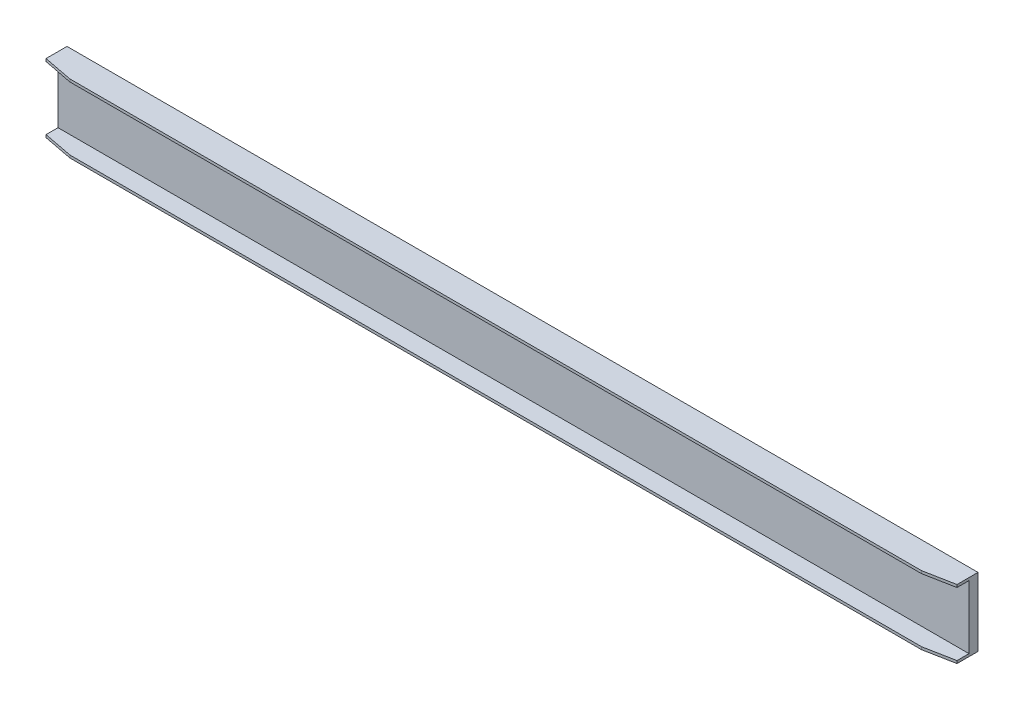
SolidWorks part; units mm, degrees
ref_plane "前视" through (0, 0, 0) normal (0, 0, 1) x (1, 0, 0)
ref_plane "上视" through (0, 0, 0) normal (0, 1, 0) x (1, 0, 0)
ref_plane "右视" through (0, 0, 0) normal (1, 0, 0) x (0, 0, -1)
sketch "草图1" plane through (0, 0, 0) normal (0, 0, 1) x (1, 0, 0)
  line L0 (0, 280.187) -> (0, -298.191) construction
  line L1 (-2057.2074, 0) -> (2116.7847, 0) construction
  line L2 (2116.7847, 80) -> (-2430.1435, 80) construction
  line L3 (-1995, 150) -> (1995, 150)
  line L5 (-1995, -150) -> (1995, -150)
  line L6 (1995, 150) -> (1995, -150)
  line L7 (-2430.1435, -80) -> (2116.7847, -80) construction
  line L8 (1940, 266.4652) -> (1940, -249.2739) construction
  line L9 (1860, -249.2739) -> (1860, 266.4652) construction
  line L10 (1060, 266.4652) -> (1060, -361.7988) construction
  line L11 (1780, 266.4652) -> (1780, -249.2739) construction
  line L12 (1780, -249.2739) -> (1700, -249.2739) construction
  line L13 (1700, -249.2739) -> (1700, 266.4652) construction
  line L14 (1540, 266.4652) -> (1540, -361.7988) construction
  line L15 (1380, 266.4652) -> (1380, -361.7988) construction
  line L16 (1220, -361.7988) -> (1220, 266.4652) construction
  line L17 (980, -361.7988) -> (980, 266.4652) construction
  line L18 (740, -361.7988) -> (740, 464.33) construction
  line L19 (820, 266.4652) -> (820, -361.7988) construction
  line L20 (580, -361.7988) -> (580, 266.4652) construction
  line L21 (420, -361.7988) -> (420, 266.4652) construction
  line L22 (300, -298.191) -> (300, 266.4652) construction
  line L23 (60, 280.187) -> (60, -298.191) construction
  line L24 (140, 280.187) -> (140, -298.191) construction
  line L25 (220, -298.191) -> (220, 280.187) construction
  line L26 (-1995, 150) -> (-1995, -150)
  circle A0 centre (1940, 80) radius 13
  circle A1 centre (1860, 80) radius 13
  circle A2 centre (1780, 80) radius 13
  circle A3 centre (1700, 80) radius 13
  circle A4 centre (1540, 80) radius 11.5
  circle A5 centre (1380, 80) radius 11.5
  circle A6 centre (1220, 80) radius 11.5
  circle A7 centre (1060, 80) radius 11.5
  circle A8 centre (980, 80) radius 11.5
  circle A9 centre (820, 80) radius 11.5
  circle A10 centre (740, 80) radius 11.5
  circle A11 centre (580, 80) radius 11.5
  circle A12 centre (980, 0) radius 11.5
  circle A13 centre (1060, 0) radius 11.5
  circle A14 centre (820, 0) radius 11.5
  circle A15 centre (740, 0) radius 11.5
  circle A16 centre (580, 0) radius 11.5
  circle A17 centre (1220, 0) radius 11.5
  circle A18 centre (1380, 0) radius 11.5
  circle A19 centre (1540, 0) radius 11.5
  circle A20 centre (1700, 0) radius 13
  circle A21 centre (1780, 0) radius 13
  circle A22 centre (1860, 0) radius 13
  circle A23 centre (1940, 0) radius 13
  circle A24 centre (420, 80) radius 11.5
  circle A25 centre (420, 0) radius 11.5
  circle A26 centre (300, 0) radius 11.5
  circle A27 centre (300, 80) radius 11.5
  circle A28 centre (220, 80) radius 11.5
  circle A29 centre (220, 0) radius 11.5
  circle A30 centre (140, 0) radius 13
  circle A31 centre (140, 80) radius 13
  circle A32 centre (60, 80) radius 13
  circle A33 centre (60, 0) radius 13
  circle A34 centre (1700, -80) radius 13
  circle A35 centre (1780, -80) radius 13
  circle A36 centre (1860, -80) radius 13
  circle A37 centre (1940, -80) radius 13
  circle A38 centre (580, -80) radius 11.5
  circle A39 centre (740, -80) radius 11.5
  circle A40 centre (820, -80) radius 11.5
  circle A41 centre (980, -80) radius 11.5
  circle A42 centre (1060, -80) radius 11.5
  circle A43 centre (1220, -80) radius 11.5
  circle A44 centre (1380, -80) radius 11.5
  circle A45 centre (1540, -80) radius 11.5
  circle A46 centre (220, -80) radius 11.5
  circle A47 centre (300, -80) radius 11.5
  circle A48 centre (420, -80) radius 11.5
  circle A49 centre (580, -80) radius 11.5
  circle A50 centre (60, -80) radius 13
  circle A51 centre (140, -80) radius 13
  circle A52 centre (-140, -80) radius 13
  circle A53 centre (-60, -80) radius 13
  circle A54 centre (-580, -80) radius 11.5
  circle A55 centre (-420, -80) radius 11.5
  circle A56 centre (-300, -80) radius 11.5
  circle A57 centre (-220, -80) radius 11.5
  circle A58 centre (-1540, -80) radius 11.5
  circle A59 centre (-1380, -80) radius 11.5
  circle A60 centre (-1220, -80) radius 11.5
  circle A61 centre (-1060, -80) radius 11.5
  circle A62 centre (-980, -80) radius 11.5
  circle A63 centre (-820, -80) radius 11.5
  circle A64 centre (-740, -80) radius 11.5
  circle A65 centre (-580, -80) radius 11.5
  circle A66 centre (-1940, -80) radius 13
  circle A67 centre (-1860, -80) radius 13
  circle A68 centre (-1780, -80) radius 13
  circle A69 centre (-1700, -80) radius 13
  circle A70 centre (-60, 0) radius 13
  circle A71 centre (-60, 80) radius 13
  circle A72 centre (-140, 80) radius 13
  circle A73 centre (-140, 0) radius 13
  circle A74 centre (-220, 0) radius 11.5
  circle A75 centre (-220, 80) radius 11.5
  circle A76 centre (-300, 80) radius 11.5
  circle A77 centre (-300, 0) radius 11.5
  circle A78 centre (-420, 0) radius 11.5
  circle A79 centre (-420, 80) radius 11.5
  circle A80 centre (-1940, 0) radius 13
  circle A81 centre (-1860, 0) radius 13
  circle A82 centre (-1780, 0) radius 13
  circle A83 centre (-1700, 0) radius 13
  circle A84 centre (-1540, 0) radius 11.5
  circle A85 centre (-1380, 0) radius 11.5
  circle A86 centre (-1220, 0) radius 11.5
  circle A87 centre (-580, 0) radius 11.5
  circle A88 centre (-740, 0) radius 11.5
  circle A89 centre (-820, 0) radius 11.5
  circle A90 centre (-1060, 0) radius 11.5
  circle A91 centre (-980, 0) radius 11.5
  circle A92 centre (-580, 80) radius 11.5
  circle A93 centre (-740, 80) radius 11.5
  circle A94 centre (-820, 80) radius 11.5
  circle A95 centre (-980, 80) radius 11.5
  circle A96 centre (-1060, 80) radius 11.5
  circle A97 centre (-1220, 80) radius 11.5
  circle A98 centre (-1380, 80) radius 11.5
  circle A99 centre (-1540, 80) radius 11.5
  circle A100 centre (-1700, 80) radius 13
  circle A101 centre (-1780, 80) radius 13
  circle A102 centre (-1860, 80) radius 13
  circle A103 centre (-1940, 80) radius 13
  dimension "D22" = 23
  dimension "D23" = 26
  dimension "D24" = 26
  dimension "D1" = 3990
  dimension "D2" = 300
  dimension "D3" = 70
  dimension "D4" = 80
  dimension "D5" = 55
  dimension "D6" = 80
  dimension "D7" = 80
  dimension "D8" = 80
  dimension "D9" = 455
  dimension "D10" = 160
  dimension "D11" = 160
  dimension "D12" = 160
  dimension "D13" = 80
  dimension "D14" = 160
  dimension "D15" = 80
  dimension "D16" = 160
  dimension "D17" = 160
  dimension "D18" = 120
  dimension "D19" = 60
  dimension "D20" = 80
  dimension "D21" = 80
extrude "基体-拉伸" add sketch "草图1" along normal blind 39.5
sketch "草图2" plane through (0, 0, 39.5) normal (0, 0, 1) x (1, 0, 0)
  line L0 (1995, -150) -> (1995, 150) construction
  line L1 (-1995, 150) -> (1995, 150)
  line L2 (-1995, 150) -> (-1995, 138.5)
  line L3 (-1995, 138.5) -> (1995, 138.5)
  line L4 (1995, 150) -> (1995, 138.5)
  line L5 (0, 0) -> (2507.3409, 0) construction
  line L6 (1995, -150) -> (1995, -138.5)
  line L7 (-1995, -138.5) -> (1995, -138.5)
  line L8 (-1995, -150) -> (-1995, -138.5)
  line L9 (-1995, -150) -> (1995, -150)
  dimension "D1" = 11.5
extrude "凸台-拉伸1" add sketch "草图2" along normal blind 77.5
sketch "草图3" plane through (0, 0, 0) normal (0, 0, -1) x (-1, 0, 0)
  line L0 (0, 0) -> (2381.8358, 0) construction
  line L1 (0, 348.8193) -> (0, -302.4645) construction
  line L2 (1300, 348.8193) -> (1300, -385.903) construction
  line L3 (1995, 150) -> (1995, -150) construction
  line L4 (900, 237.7997) -> (900, -385.903) construction
  line L5 (1265, 115) -> (1335, 115)
  line L6 (1265, 115) -> (1265, -115)
  line L7 (1265, -115) -> (1335, -115)
  line L8 (1335, 115) -> (1335, -115)
  line L9 (865, 115) -> (935, 115)
  line L10 (865, 115) -> (865, -115)
  line L11 (865, -115) -> (935, -115)
  line L12 (935, 115) -> (935, -115)
  line L13 (500, -385.903) -> (500, 237.7997) construction
  line L14 (-1265, 115) -> (-1335, 115)
  line L15 (535, -115) -> (465, -115)
  line L16 (535, -115) -> (535, 115)
  line L17 (535, 115) -> (465, 115)
  line L18 (465, -115) -> (465, 115)
  line L19 (-1335, 115) -> (-1335, -115)
  line L20 (-1265, 115) -> (-1265, -115)
  line L21 (-1265, -115) -> (-1335, -115)
  line L22 (-865, -115) -> (-935, -115)
  line L23 (-935, 115) -> (-935, -115)
  line L24 (-865, 115) -> (-935, 115)
  line L25 (-865, 115) -> (-865, -115)
  line L26 (-535, -115) -> (-535, 115)
  line L27 (-535, -115) -> (-465, -115)
  line L28 (-465, -115) -> (-465, 115)
  line L29 (-535, 115) -> (-465, 115)
  dimension "D1" = 695
  dimension "D2" = 70
  dimension "D3" = 230
  dimension "D4" = 400
  dimension "D5" = 70
  dimension "D6" = 230
  dimension "D7" = 400
  dimension "D8" = 70
  dimension "D9" = 230
extrude "凸台-拉伸2" add sketch "草图3" along normal blind 16
sketch "草图4" plane through (0, 0, 39.5) normal (0, 0, 1) x (1, 0, 0)
  line L0 (0, 0) -> (2249.2348, 0) construction
  line L1 (0, 0) -> (0, 1256.1111) construction
  line L2 (1300, 296.2067) -> (1300, -332.3633) construction
  line L3 (900, -332.3633) -> (900, 296.2067) construction
  line L4 (1995, -138.5) -> (1995, 138.5) construction
  line L5 (500, 260.05) -> (500, -332.3633) construction
  line L6 (1458.5104, 80) -> (376.6321, 80) construction
  circle A0 centre (1300, 80) radius 13
  circle A1 centre (900, 80) radius 13
  circle A2 centre (900, 0) radius 13
  circle A3 centre (1300, 0) radius 13
  circle A4 centre (900, -80) radius 13
  circle A5 centre (1300, -80) radius 13
  circle A6 centre (500, 80) radius 13
  circle A7 centre (500, 0) radius 13
  circle A8 centre (500, -80) radius 13
  circle A9 centre (-500, -80) radius 13
  circle A10 centre (-500, 0) radius 13
  circle A11 centre (-500, 80) radius 13
  circle A12 centre (-1300, -80) radius 13
  circle A13 centre (-900, -80) radius 13
  circle A14 centre (-1300, 0) radius 13
  circle A15 centre (-900, 0) radius 13
  circle A16 centre (-900, 80) radius 13
  circle A17 centre (-1300, 80) radius 13
  dimension "D5" = 26
  dimension "D1" = 695
  dimension "D2" = 400
  dimension "D3" = 400
  dimension "D4" = 80
extrude "切除-拉伸1" cut sketch "草图4" against normal through all
sketch "草图5" plane through (0, 150, 0) normal (0, 1, 0) x (-1, 0, 0)
  line L0 (-1995, 92) -> (-1995, 117)
  line L1 (-1995, 117) -> (-1995, 0) construction
  line L2 (-1995, 117) -> (-1865, 117)
  line L3 (-1995, 117) -> (1995, 117) construction
  line L4 (-1865, 117) -> (-1995, 92)
  line L5 (0, 174.8481) -> (0, -119.4889) construction
  line L6 (1865, 117) -> (1995, 92)
  line L7 (1995, 117) -> (1865, 117)
  line L8 (1995, 92) -> (1995, 117)
  dimension "D1" = 130
  dimension "D2" = 25
extrude "切除-拉伸2" cut sketch "草图5" against normal through all
sketch "草图6" plane through (0, 0, 39.5) normal (0, 0, 1) x (1, 0, 0)
  line L1 (-1995, 138.5) -> (1995, 138.5)
  line L2 (-1995, 138.5) -> (-1995, -138.5)
  line L3 (-1995, -138.5) -> (1995, -138.5)
  line L4 (1995, 138.5) -> (1995, -138.5)
extrude "凸台-拉伸3" add sketch "草图6" against normal blind 39.5
sketch "草图7" plane through (0, 0, 0) normal (0, 0, -1) x (-1, 0, 0)
  line L1 (-1335, 115) -> (-1265, 115)
  line L2 (-1335, 115) -> (-1335, -115)
  line L3 (-1335, -115) -> (-1265, -115)
  line L4 (-1265, 115) -> (-1265, -115)
  line L5 (-935, 115) -> (-865, 115)
  line L6 (-935, 115) -> (-935, -115)
  line L7 (-935, -115) -> (-865, -115)
  line L8 (-865, 115) -> (-865, -115)
  line L9 (-535, 115) -> (-465, 115)
  line L10 (-535, 115) -> (-535, -115)
  line L11 (-535, -115) -> (-465, -115)
  line L12 (-465, 115) -> (-465, -115)
  line L13 (465, 115) -> (535, 115)
  line L14 (465, 115) -> (465, -115)
  line L15 (465, -115) -> (535, -115)
  line L16 (535, 115) -> (535, -115)
  line L17 (865, 115) -> (935, 115)
  line L18 (865, 115) -> (865, -115)
  line L19 (865, -115) -> (935, -115)
  line L20 (935, 115) -> (935, -115)
  line L21 (1265, 115) -> (1335, 115)
  line L22 (1265, 115) -> (1265, -115)
  line L23 (1265, -115) -> (1335, -115)
  line L24 (1335, 115) -> (1335, -115)
extrude "凸台-拉伸4" add sketch "草图7" along normal blind 16
